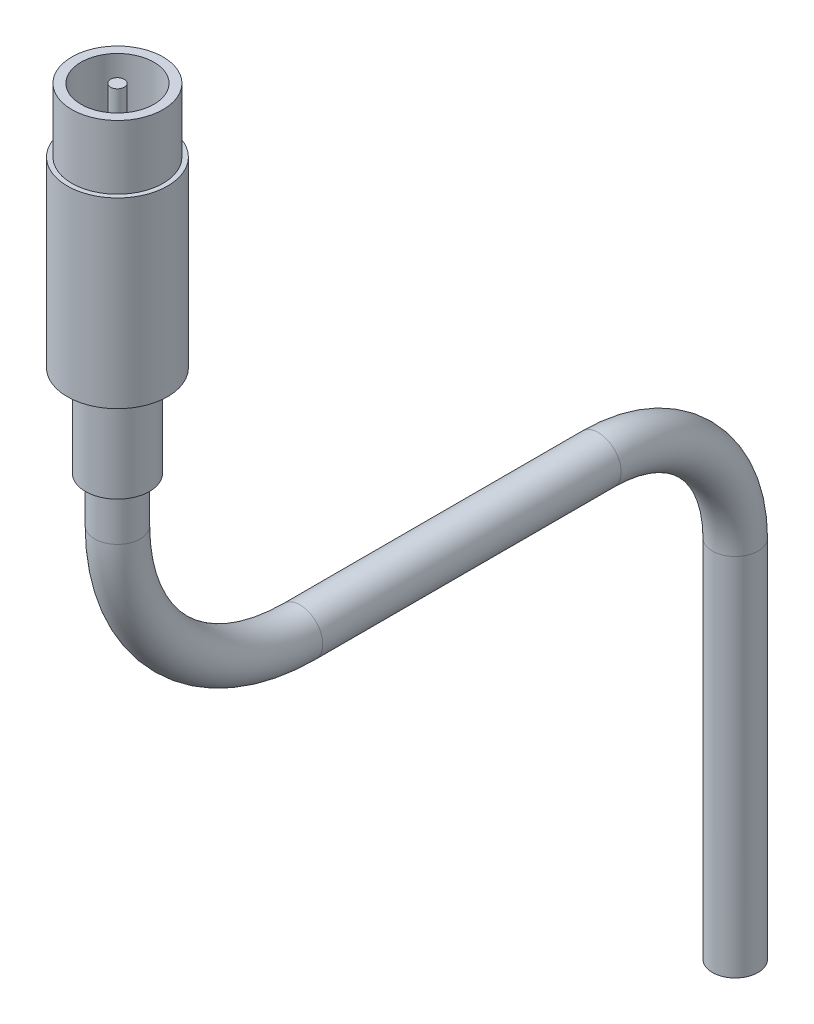
SolidWorks part; units mm, degrees
ref_plane "Front Plane" through (0, 0, 0) normal (0, 0, 1) x (1, 0, 0)
ref_plane "Top Plane" through (0, 0, 0) normal (0, 1, 0) x (1, 0, 0)
ref_plane "Right Plane" through (0, 0, 0) normal (1, 0, 0) x (0, 0, -1)
sketch "Sketch1" plane through (0, 0, 0) normal (0, 1, 0) x (1, 0, 0)
  circle A0 centre (0, 0) radius 5.5
extrude "Handle" add sketch "Sketch1" against normal blind 20
sketch "Sketch2" plane through (0, 0, 0) normal (0, 1, 0) x (1, 0, 0)
  circle A0 centre (0, 0) radius 5
  circle A1 centre (0, 0) radius 4
extrude "Sleeve" add sketch "Sketch2" along normal blind 7
sketch "Sketch3" plane through (0, 0, 0) normal (0, 1, 0) x (1, 0, 0)
  circle A0 centre (0, 0) radius 0.75
extrude "Centre_pin" add sketch "Sketch3" along normal blind 7
ref_plane "Plane_ym20" through (0, -20, 0) normal (0, 1, 0) x (1, 0, 0)
sketch "Sketch4" plane through (0, -20, 0) normal (0, 1, 0) x (1, 0, 0)
  circle A0 centre (0, 0) radius 3.5
extrude "Strain_relief" add sketch "Sketch4" against normal blind 10
sketch "Sketch5" plane through (0, 0, 0) normal (1, 0, 0) x (0, 0, -1)
  line L0 (0, -30) -> (0, -35)
  line L1 (20, -55) -> (52.7, -55)
  line L2 (67.7, -70) -> (67.7, -110)
  arc A0 (0, -35) -> (20, -55) centre (20, -35) ccw
  arc A1 (52.7, -55) -> (67.7, -70) centre (52.7, -70) cw
sweep "Lead" add path "Sketch5" circular profile diameter 5 parameters "D3"=5
